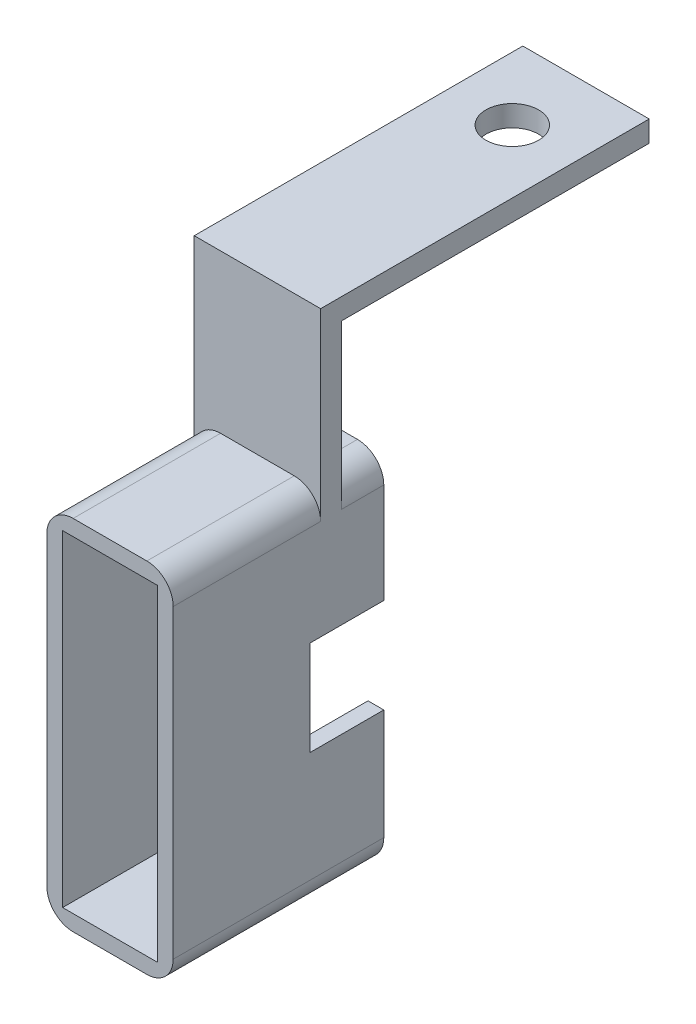
SolidWorks part; units mm, degrees
ref_plane "Plan de face" through (0, 0, 0) normal (0, 0, 1) x (1, 0, 0)
ref_plane "Plan de dessus" through (0, 0, 0) normal (0, 1, 0) x (1, 0, 0)
ref_plane "Plan de droite" through (0, 0, 0) normal (1, 0, 0) x (0, 0, -1)
sketch "Esquisse1" plane through (0, 0, 0) normal (0, 0, 1) x (1, 0, 0)
  line L0 (-20.7757, 15.7218) -> (-20.7757, -15.2782)
  line L1 (-11.7757, 15.7218) -> (-11.7757, -15.2782)
  line L2 (-20.7757, 15.7218) -> (-11.7757, 15.7218)
  line L3 (-20.7757, -15.2782) -> (-11.7757, -15.2782)
  line L4 (-22.2757, 15.7218) -> (-22.2757, -12.7782)
  line L5 (-22.2757, -12.7782) -> (-22.2757, -16.7782)
  line L6 (-22.2757, -16.7782) -> (-10.2757, -16.7782)
  line L7 (-10.2757, -16.7782) -> (-10.2757, 17.2218)
  line L8 (-10.2757, 17.2218) -> (-22.2757, 17.2218)
  line L9 (-22.2757, 17.2218) -> (-22.2757, 15.7218)
  dimension "D1" = 31
  dimension "D2" = 31
  dimension "D3" = 9
  dimension "D4" = 1.5
  dimension "D5" = 34
  dimension "D6" = 1.5
extrude "Boss.-Extru.1" add sketch "Esquisse1" along normal blind 20
sketch "Esquisse3" plane through (0, 17.2218, 0) normal (0, 1, 0) x (1, 0, 0)
  line L0 (-22.2757, -4) -> (-10.2757, -4)
  line L1 (-22.2757, -20) -> (-22.2757, 0) construction
  line L2 (-10.2757, -20) -> (-10.2757, 0) construction
  line L6 (-10.2757, 0) -> (-22.2757, 0) construction
  line L7 (-22.2757, -4) -> (-22.2757, -6)
  line L8 (-22.2757, -6) -> (-10.2757, -6)
  line L9 (-10.2757, -6) -> (-10.2757, -4)
  dimension "D1" = 2
  dimension "D2" = 4
extrude "Boss.-Extru.2" add sketch "Esquisse3" along normal blind 15
sketch "Esquisse4" plane through (0, 0, 4) normal (0, 0, -1) x (-1, 0, 0)
  line L0 (10.2757, 30.2218) -> (22.2757, 30.2218)
  line L1 (10.2757, 32.2218) -> (10.2757, 17.2218) construction
  line L2 (22.2757, 32.2218) -> (22.2757, 17.2218) construction
  line L3 (22.2757, 30.2218) -> (22.2757, 32.2218)
  line L4 (22.2757, 32.2218) -> (10.2757, 32.2218)
  line L5 (10.2757, 32.2218) -> (10.2757, 30.2218)
  dimension "D1" = 2
extrude "Boss.-Extru.3" add sketch "Esquisse4" along normal blind 29.2
sketch "Esquisse5" plane through (0, 32.2218, 0) normal (0, 1, 0) x (1, 0, 0)
  line L0 (-16.2757, -6) -> (-16.2757, 25.2) construction
  line L1 (-22.2757, -6) -> (-10.2757, -6) construction
  line L2 (-22.2757, 25.2) -> (-10.2757, 25.2) construction
  circle A0 centre (-16.2757, 18.2) radius 2.5
  dimension "D1" = 7
extrude "Enlèv. mat.-Extru.3" cut sketch "Esquisse5" against normal blind 10
fillet "Congé1" radius 2.5 2 edges at (-10.2757, -16.7782, 10) (-10.2757, 17.2218, 13)
fillet "Congé2" radius 2.5 4 edges at (-22.2757, 17.2218, 2) (-22.2757, -16.7782, 10) (-22.2757, 17.2218, 13) (-10.2757, 17.2218, 2)
sketch "Esquisse6" plane through (-22.2757, 0, 0) normal (-1, 0, 0) x (0, 0, 1)
  line L0 (0, 7.2218) -> (7, 7.2218)
  line L1 (0, 14.7218) -> (0, -14.2782) construction
  line L2 (7, 7.2218) -> (7, -3.7782)
  line L3 (7, -3.7782) -> (0, -3.7782)
  line L4 (0, -14.2782) -> (20, -14.2782) construction
  line L5 (4, 14.7218) -> (0, 14.7218) construction
  line M6 (0, 14.7218) -> (0, -14.2782)
  dimension "D1" = 10.5
  dimension "D2" = 7.5
  dimension "D3" = 7
extrude "Enlèv. mat.-Extru.5" cut sketch "Esquisse6" against normal blind 5 and the other way through all contours L3 L2 L0 M6
sketch "Esquisse2" plane through (-10.2757, 0, 0) normal (1, 0, 0) x (0, 0, -1)
  line L0 (0, -3.7782) -> (-7, -3.7782)
  line L1 (0, -14.2782) -> (0, 14.7218) construction
  line L2 (-7, -3.7782) -> (-7, 5.2218)
  line L3 (-7, 5.2218) -> (0, 5.2218)
  line L4 (-20, 17.2218) -> (0, 17.2218) construction
  line L5 (-20, -16.7782) -> (0, -16.7782) construction
  line M3 (0, -14.2782) -> (0, 14.7218)
  dimension "D1" = 12
  dimension "D2" = 13
  dimension "D3" = 7
extrude "Enlèv. mat.-Extru.2" cut sketch "Esquisse2" against normal blind 5 and the other way through all contours L3 L2 L0 M3
